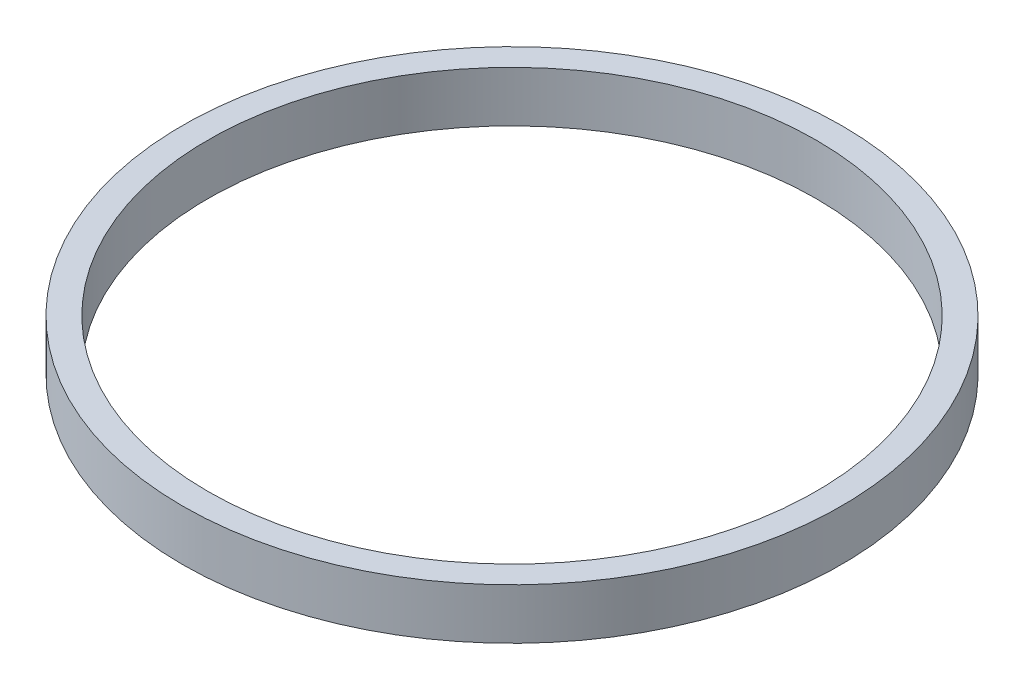
SolidWorks part; units mm, degrees
ref_plane "Plan de face" through (0, 0, 0) normal (0, 0, 1) x (1, 0, 0)
ref_plane "Plan de dessus" through (0, 0, 0) normal (0, 1, 0) x (1, 0, 0)
ref_plane "Plan de droite" through (0, 0, 0) normal (1, 0, 0) x (0, 0, -1)
sketch "Esquisse1" plane through (0, 0, 0) normal (0, 1, 0) x (1, 0, 0)
  circle A0 centre (0, 0) radius 6
  circle A1 centre (0, 0) radius 6.5
  dimension "D1" = 12
  dimension "D2" = 13
extrude "Boss.-Extru.1" add sketch "Esquisse1" along normal blind 1
